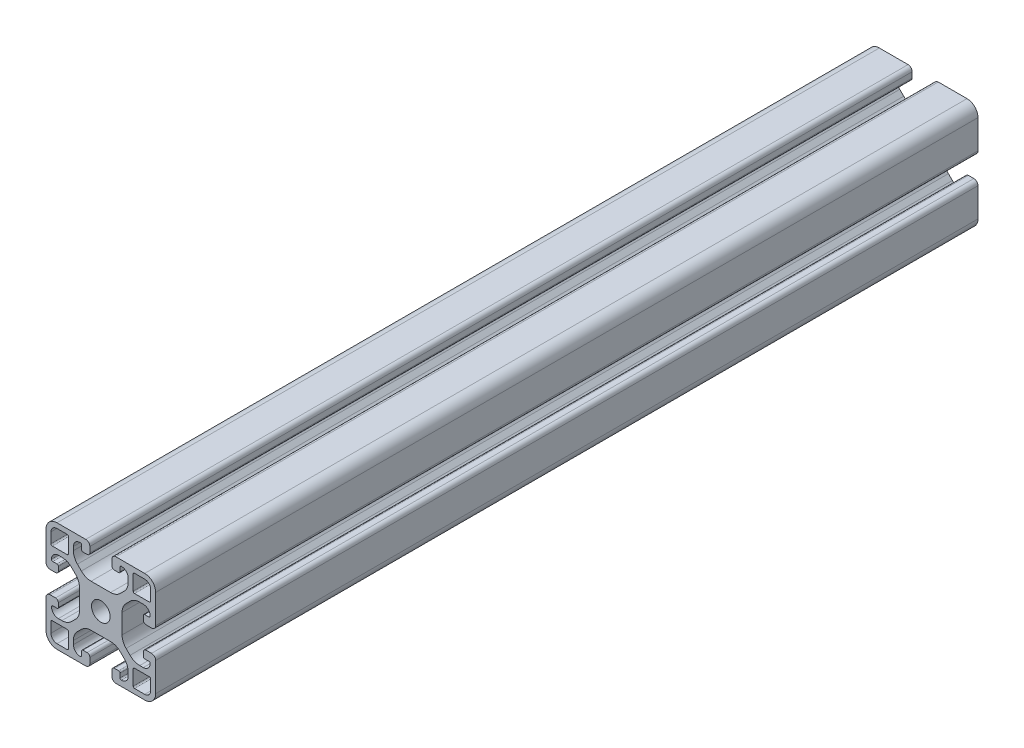
SolidWorks part; units mm, degrees
ref_plane "Front Plane" through (0, 0, 0) normal (0, 0, 1) x (1, 0, 0)
ref_plane "Top Plane" through (0, 0, 0) normal (0, 1, 0) x (1, 0, 0)
ref_plane "Right Plane" through (0, 0, 0) normal (1, 0, 0) x (0, 0, -1)
sketch "Sketch1" plane through (0, 0, 0) normal (0, 0, 1) x (1, 0, 0)
  line L0 (1.8, 4) -> (1.8, 7.7)
  line L1 (2.3, 8.2) -> (7.7, 8.2)
  line L2 (8.2, 7.7) -> (8.2, 2.3)
  line L3 (7.7, 1.8) -> (4, 1.8)
  line L4 (4, 38.2) -> (7.7, 38.2)
  line L5 (8.2, 37.7) -> (8.2, 32.3)
  line L6 (7.7, 31.8) -> (2.3, 31.8)
  line L7 (1.8, 32.3) -> (1.8, 36)
  line L8 (31.8, 32.3) -> (31.8, 37.7)
  line L9 (32.3, 38.2) -> (36, 38.2)
  line L10 (38.2, 36) -> (38.2, 32.3)
  line L11 (37.7, 31.8) -> (32.3, 31.8)
  line L12 (32.3, 8.2) -> (37.7, 8.2)
  line L13 (38.2, 7.7) -> (38.2, 4)
  line L14 (36, 1.8) -> (32.3, 1.8)
  line L15 (31.8, 2.3) -> (31.8, 7.7)
  line L16 (0, 36) -> (0, 25.5)
  line L17 (1.5, 24) -> (3.5, 24)
  line L18 (4.5, 25) -> (4.5, 26.5)
  line L19 (4, 27) -> (2.5, 27)
  line L20 (4.5, 30) -> (5.8076, 30)
  line L21 (9.3431, 28.5355) -> (10.7855, 27.0931)
  line L22 (12.25, 23.5576) -> (12.25, 16.4424)
  line L23 (10.7855, 12.9069) -> (9.3431, 11.4645)
  line L24 (5.8076, 10) -> (4.5, 10)
  line L25 (2.5, 13) -> (4, 13)
  line L26 (4.5, 13.5) -> (4.5, 15)
  line L27 (3.5, 16) -> (1.5, 16)
  line L28 (0, 14.5) -> (0, 4)
  line L29 (4, 0) -> (14.5, 0)
  line L30 (16, 1.5) -> (16, 3.5)
  line L31 (15, 4.5) -> (13.5, 4.5)
  line L32 (13, 4) -> (13, 2.5)
  line L33 (10, 4.5) -> (10, 5.8076)
  line L34 (11.4645, 9.3431) -> (12.9069, 10.7855)
  line L35 (16.4424, 12.25) -> (23.5576, 12.25)
  line L36 (27.0931, 10.7855) -> (28.5355, 9.3431)
  line L37 (30, 5.8076) -> (30, 4.5)
  line L38 (27, 2.5) -> (27, 4)
  line L39 (26.5, 4.5) -> (25, 4.5)
  line L40 (24, 3.5) -> (24, 1.5)
  line L41 (25.5, 0) -> (36, 0)
  line L42 (40, 4) -> (40, 14.5)
  line L43 (38.5, 16) -> (36.5, 16)
  line L44 (35.5, 15) -> (35.5, 13.5)
  line L45 (36, 13) -> (37.5, 13)
  line L46 (35.5, 10) -> (34.1924, 10)
  line L47 (30.6569, 11.4645) -> (29.2145, 12.9069)
  line L48 (27.75, 16.4424) -> (27.75, 23.5576)
  line L49 (29.2145, 27.0931) -> (30.6569, 28.5355)
  line L50 (34.1924, 30) -> (35.5, 30)
  line L51 (37.5, 27) -> (36, 27)
  line L52 (35.5, 26.5) -> (35.5, 25)
  line L53 (36.5, 24) -> (38.5, 24)
  line L54 (40, 25.5) -> (40, 36)
  line L55 (36, 40) -> (25.5, 40)
  line L56 (24, 38.5) -> (24, 36.5)
  line L57 (25, 35.5) -> (26.5, 35.5)
  line L58 (27, 36) -> (27, 37.5)
  line L59 (30, 35.5) -> (30, 34.1924)
  line L60 (28.5355, 30.6569) -> (27.0931, 29.2145)
  line L61 (23.5576, 27.75) -> (16.4424, 27.75)
  line L62 (12.9069, 29.2145) -> (11.4645, 30.6569)
  line L63 (10, 34.1924) -> (10, 35.5)
  line L64 (13, 37.5) -> (13, 36)
  line L65 (13.5, 35.5) -> (15, 35.5)
  line L66 (16, 36.5) -> (16, 38.5)
  line L67 (14.5, 40) -> (4, 40)
  arc A0 (1.8, 7.7) -> (2.3, 8.2) centre (2.3, 7.7) cw
  arc A1 (7.7, 8.2) -> (8.2, 7.7) centre (7.7, 7.7) cw
  arc A2 (8.2, 2.3) -> (7.7, 1.8) centre (7.7, 2.3) cw
  arc A3 (4, 1.8) -> (1.8, 4) centre (4, 4) cw
  arc A4 (1.8, 36) -> (4, 38.2) centre (4, 36) cw
  arc A5 (7.7, 38.2) -> (8.2, 37.7) centre (7.7, 37.7) cw
  arc A6 (8.2, 32.3) -> (7.7, 31.8) centre (7.7, 32.3) cw
  arc A7 (2.3, 31.8) -> (1.8, 32.3) centre (2.3, 32.3) cw
  circle A8 centre (20, 20) radius 3.4
  arc A9 (31.8, 37.7) -> (32.3, 38.2) centre (32.3, 37.7) cw
  arc A10 (36, 38.2) -> (38.2, 36) centre (36, 36) cw
  arc A11 (38.2, 32.3) -> (37.7, 31.8) centre (37.7, 32.3) cw
  arc A12 (32.3, 31.8) -> (31.8, 32.3) centre (32.3, 32.3) cw
  arc A13 (31.8, 7.7) -> (32.3, 8.2) centre (32.3, 7.7) cw
  arc A14 (37.7, 8.2) -> (38.2, 7.7) centre (37.7, 7.7) cw
  arc A15 (38.2, 4) -> (36, 1.8) centre (36, 4) cw
  arc A16 (32.3, 1.8) -> (31.8, 2.3) centre (32.3, 2.3) cw
  arc A17 (0, 25.5) -> (1.5, 24) centre (1.5, 25.5) ccw
  arc A18 (3.5, 24) -> (4.5, 25) centre (3.5, 25) ccw
  arc A19 (4.5, 26.5) -> (4, 27) centre (4, 26.5) ccw
  arc A20 (2.5, 27) -> (2, 27.5) centre (2.5, 27.5) cw
  arc A21 (2, 27.5) -> (4.5, 30) centre (4.5, 27.5) cw
  arc A22 (5.8076, 30) -> (9.3431, 28.5355) centre (5.8076, 25) cw
  arc A23 (10.7855, 27.0931) -> (12.25, 23.5576) centre (7.25, 23.5576) cw
  arc A24 (12.25, 16.4424) -> (10.7855, 12.9069) centre (7.25, 16.4424) cw
  arc A25 (9.3431, 11.4645) -> (5.8076, 10) centre (5.8076, 15) cw
  arc A26 (4.5, 10) -> (2, 12.5) centre (4.5, 12.5) cw
  arc A27 (2, 12.5) -> (2.5, 13) centre (2.5, 12.5) cw
  arc A28 (4, 13) -> (4.5, 13.5) centre (4, 13.5) ccw
  arc A29 (4.5, 15) -> (3.5, 16) centre (3.5, 15) ccw
  arc A30 (1.5, 16) -> (0, 14.5) centre (1.5, 14.5) ccw
  arc A31 (0, 4) -> (4, 0) centre (4, 4) ccw
  arc A32 (14.5, 0) -> (16, 1.5) centre (14.5, 1.5) ccw
  arc A33 (16, 3.5) -> (15, 4.5) centre (15, 3.5) ccw
  arc A34 (13.5, 4.5) -> (13, 4) centre (13.5, 4) ccw
  arc A35 (13, 2.5) -> (12.5, 2) centre (12.5, 2.5) cw
  arc A36 (12.5, 2) -> (10, 4.5) centre (12.5, 4.5) cw
  arc A37 (10, 5.8076) -> (11.4645, 9.3431) centre (15, 5.8076) cw
  arc A38 (12.9069, 10.7855) -> (16.4424, 12.25) centre (16.4424, 7.25) cw
  arc A39 (23.5576, 12.25) -> (27.0931, 10.7855) centre (23.5576, 7.25) cw
  arc A40 (28.5355, 9.3431) -> (30, 5.8076) centre (25, 5.8076) cw
  arc A41 (30, 4.5) -> (27.5, 2) centre (27.5, 4.5) cw
  arc A42 (27.5, 2) -> (27, 2.5) centre (27.5, 2.5) cw
  arc A43 (27, 4) -> (26.5, 4.5) centre (26.5, 4) ccw
  arc A44 (25, 4.5) -> (24, 3.5) centre (25, 3.5) ccw
  arc A45 (24, 1.5) -> (25.5, 0) centre (25.5, 1.5) ccw
  arc A46 (36, 0) -> (40, 4) centre (36, 4) ccw
  arc A47 (40, 14.5) -> (38.5, 16) centre (38.5, 14.5) ccw
  arc A48 (36.5, 16) -> (35.5, 15) centre (36.5, 15) ccw
  arc A49 (35.5, 13.5) -> (36, 13) centre (36, 13.5) ccw
  arc A50 (37.5, 13) -> (38, 12.5) centre (37.5, 12.5) cw
  arc A51 (38, 12.5) -> (35.5, 10) centre (35.5, 12.5) cw
  arc A52 (34.1924, 10) -> (30.6569, 11.4645) centre (34.1924, 15) cw
  arc A53 (29.2145, 12.9069) -> (27.75, 16.4424) centre (32.75, 16.4424) cw
  arc A54 (27.75, 23.5576) -> (29.2145, 27.0931) centre (32.75, 23.5576) cw
  arc A55 (30.6569, 28.5355) -> (34.1924, 30) centre (34.1924, 25) cw
  arc A56 (35.5, 30) -> (38, 27.5) centre (35.5, 27.5) cw
  arc A57 (38, 27.5) -> (37.5, 27) centre (37.5, 27.5) cw
  arc A58 (36, 27) -> (35.5, 26.5) centre (36, 26.5) ccw
  arc A59 (35.5, 25) -> (36.5, 24) centre (36.5, 25) ccw
  arc A60 (38.5, 24) -> (40, 25.5) centre (38.5, 25.5) ccw
  arc A61 (40, 36) -> (36, 40) centre (36, 36) ccw
  arc A62 (25.5, 40) -> (24, 38.5) centre (25.5, 38.5) ccw
  arc A63 (24, 36.5) -> (25, 35.5) centre (25, 36.5) ccw
  arc A64 (26.5, 35.5) -> (27, 36) centre (26.5, 36) ccw
  arc A65 (27, 37.5) -> (27.5, 38) centre (27.5, 37.5) cw
  arc A66 (27.5, 38) -> (30, 35.5) centre (27.5, 35.5) cw
  arc A67 (30, 34.1924) -> (28.5355, 30.6569) centre (25, 34.1924) cw
  arc A68 (27.0931, 29.2145) -> (23.5576, 27.75) centre (23.5576, 32.75) cw
  arc A69 (16.4424, 27.75) -> (12.9069, 29.2145) centre (16.4424, 32.75) cw
  arc A70 (11.4645, 30.6569) -> (10, 34.1924) centre (15, 34.1924) cw
  arc A71 (10, 35.5) -> (12.5, 38) centre (12.5, 35.5) cw
  arc A72 (12.5, 38) -> (13, 37.5) centre (12.5, 37.5) cw
  arc A73 (13, 36) -> (13.5, 35.5) centre (13.5, 36) ccw
  arc A74 (15, 35.5) -> (16, 36.5) centre (15, 36.5) ccw
  arc A75 (16, 38.5) -> (14.5, 40) centre (14.5, 38.5) ccw
  arc A76 (4, 40) -> (0, 36) centre (4, 36) ccw
  dimension "D1" = 20
  dimension "D2" = 20
  dimension "D3" = 6.8
  dimension "D4" = 15.5
  dimension "D5" = 15.5
extrude "Boss-Extrude1" add sketch "Sketch1" against normal blind 300
